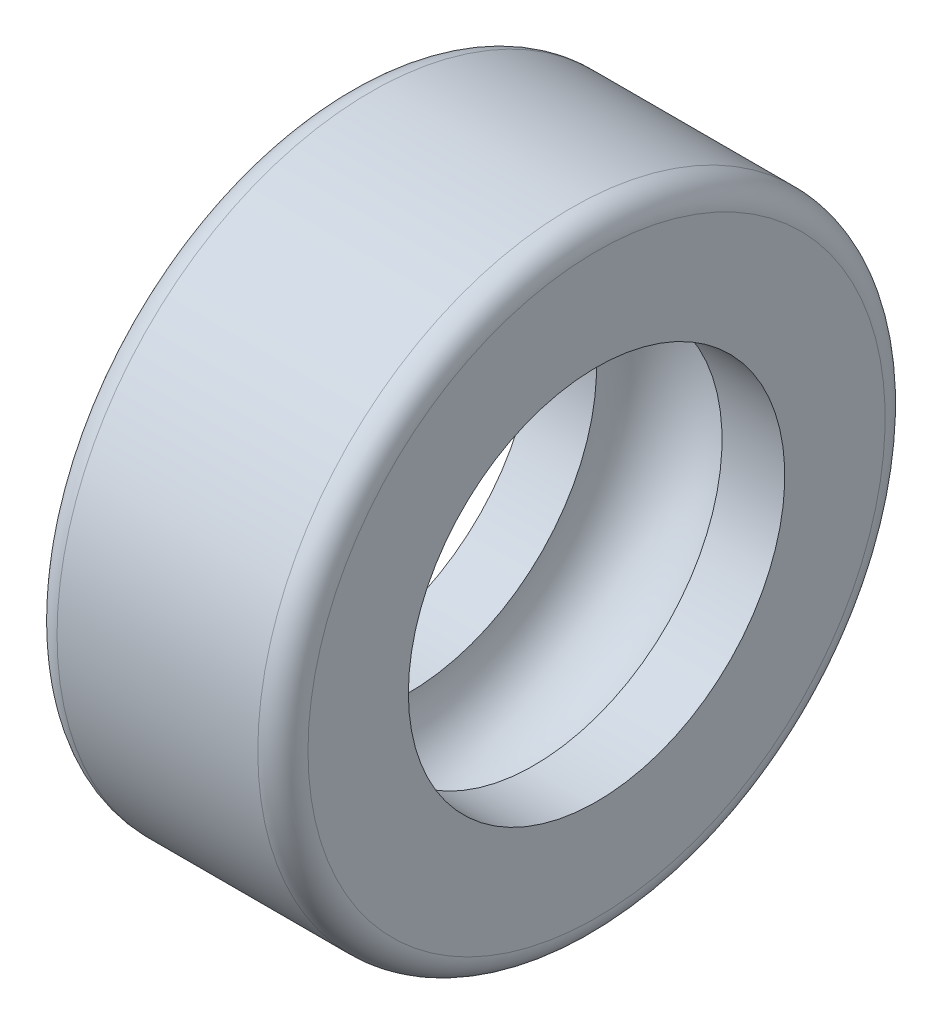
SolidWorks part; units mm, degrees
ref_plane "Front Plane" through (0, 0, 0) normal (0, 0, 1) x (1, 0, 0)
ref_plane "Top Plane" through (0, 0, 0) normal (0, 1, 0) x (1, 0, 0)
ref_plane "Right Plane" through (0, 0, 0) normal (1, 0, 0) x (0, 0, -1)
sketch "Sketch1" plane through (0, 0, 0) normal (0, 0, 1) x (1, 0, 0)
  line L0 (2.5, 7.5) -> (5, 7.5)
  line L1 (-5, 12.5) -> (5, 12.5)
  line L2 (-5, 12.5) -> (-5, 7.5)
  line L3 (-5, 7.5) -> (-2.5, 7.5)
  line L4 (5, 12.5) -> (5, 7.5)
  line L5 (0, 0) -> (14, 0) construction
  arc A0 (2.5, 7.5) -> (-2.5, 7.5) centre (0, 7.5) ccw
  dimension "D5" = 5
  dimension "D1" = 10
  dimension "D2" = 5
  dimension "D3" = 7.5
  dimension "D4" = 5
revolve "Revolve1" add sketch "Sketch1" angle 360 about L5
fillet "Fillet1" radius 1 2 edges at (5, 0, 12.5) (-5, 0, 12.5)
